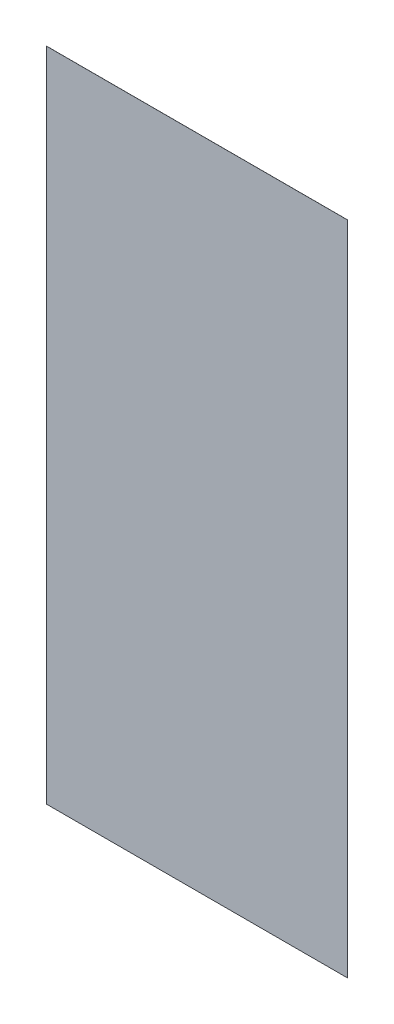
SolidWorks part; units mm, degrees
ref_plane "Front Plane" through (0, 0, 0) normal (0, 0, 1) x (1, 0, 0)
ref_plane "Top Plane" through (0, 0, 0) normal (0, 1, 0) x (1, 0, 0)
ref_plane "Right Plane" through (0, 0, 0) normal (1, 0, 0) x (0, 0, -1)
sketch "Sketch1" plane through (0, 0, 0) normal (0, 0, 1) x (1, 0, 0)
  line L0 (0, 0) -> (0, 262.89)
  line L1 (0, 262.89) -> (120.65, 262.89)
  line L2 (120.65, 262.89) -> (120.65, 0)
  line L3 (120.65, 0) -> (0, 0)
extrude "Boss-Extrude1" add sketch "Sketch1" along normal blind 0.0254
